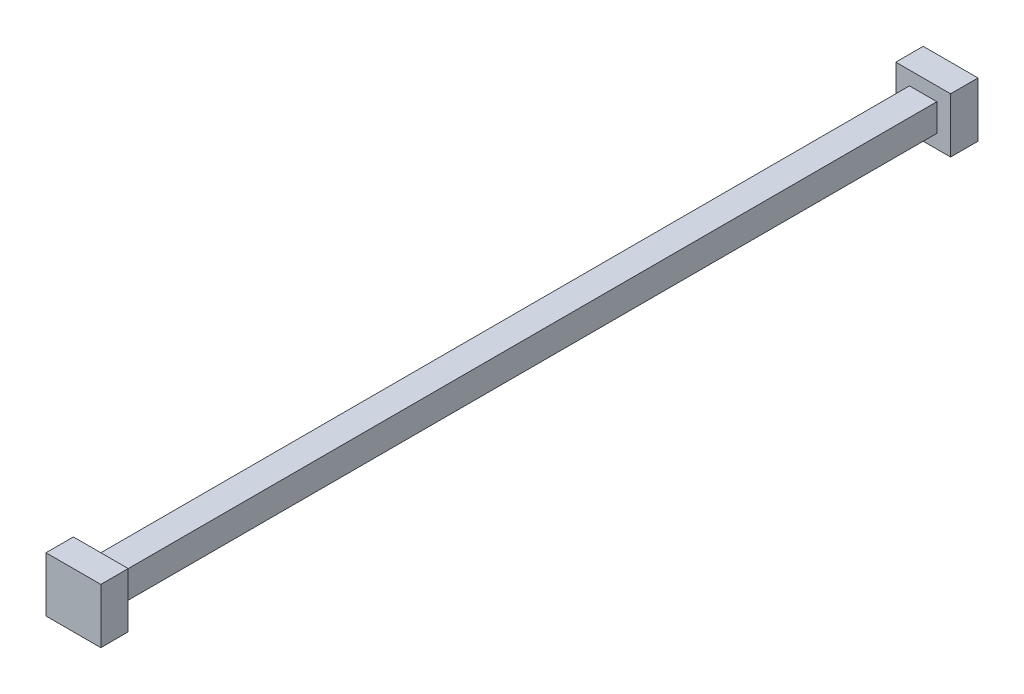
SolidWorks part; units mm, degrees
ref_plane "前视基准面" through (0, 0, 0) normal (0, 0, 1) x (1, 0, 0)
ref_plane "上视基准面" through (0, 0, 0) normal (0, 1, 0) x (1, 0, 0)
ref_plane "右视基准面" through (0, 0, 0) normal (1, 0, 0) x (0, 0, -1)
sketch "草图1" plane through (0, 0, 0) normal (0, 0, 1) x (1, 0, 0)
  line L1 (-5, -5) -> (5, -5)
  line L2 (-5, -5) -> (-5, 5)
  line L3 (-5, 5) -> (5, 5)
  line L4 (5, -5) -> (5, 5)
  line L5 (-5, -5) -> (5, 5) construction
  line L6 (-5, 5) -> (5, -5) construction
  point P0 (0, 0)
extrude "凸台-拉伸1" add sketch "草图1" along normal blind 300
sketch "草图2" plane through (0, 0, 300) normal (0, 0, 1) x (1, 0, 0)
  line L1 (-10, -10) -> (10, -10)
  line L2 (-10, -10) -> (-10, 10)
  line L3 (-10, 10) -> (10, 10)
  line L4 (10, -10) -> (10, 10)
  line L5 (-10, -10) -> (10, 10) construction
  line L6 (-10, 10) -> (10, -10) construction
  point P0 (0, 0)
extrude "凸台-拉伸2" add sketch "草图2" along normal blind 10
sketch "草图3" plane through (0, 0, 0) normal (0, 0, -1) x (-1, 0, 0)
  line L1 (-10, -10) -> (10, -10)
  line L2 (-10, -10) -> (-10, 10)
  line L3 (-10, 10) -> (10, 10)
  line L4 (10, -10) -> (10, 10)
  line L5 (-10, -10) -> (10, 10) construction
  line L6 (-10, 10) -> (10, -10) construction
  point P0 (0, 0)
extrude "凸台-拉伸3" add sketch "草图3" along normal blind 10
